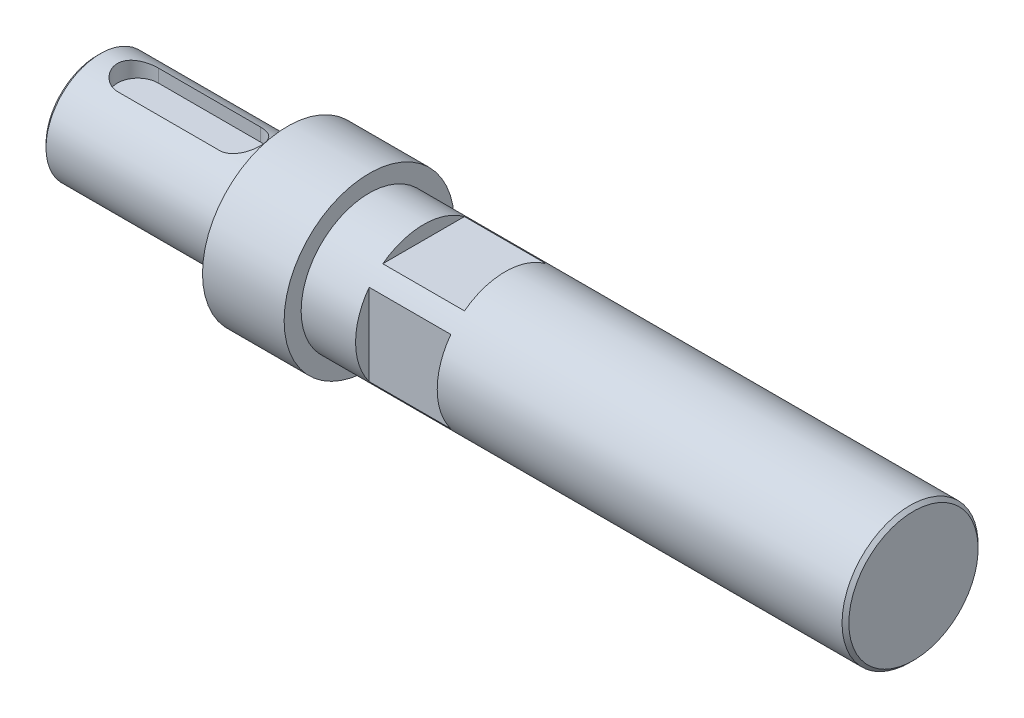
SolidWorks part; units mm, degrees
material "Простая углеродистая сталь"
ref_plane "Спереди" through (0, 0, 0) normal (0, 0, 1) x (1, 0, 0)
ref_plane "Сверху" through (0, 0, 0) normal (0, 1, 0) x (1, 0, 0)
ref_plane "Справа" through (0, 0, 0) normal (1, 0, 0) x (0, 0, -1)
sketch "Эскиз1" plane through (0, 0, 0) normal (0, 0, 1) x (1, 0, 0)
  line L0 (-178.3226, 0) -> (65.8065, 0) construction
  line L1 (0, 0) -> (0, 19)
  line L2 (-1, 20) -> (-160, 20)
  line L3 (-160, 20) -> (-160, 25)
  line L4 (-160, 25) -> (-184, 25)
  line L5 (-184, 25) -> (-184, 16)
  line L6 (-184, 16) -> (-239, 16)
  line L7 (-240, 15) -> (-240, 0)
  line L8 (-240, 0) -> (0, 0)
  line L9 (0, 19) -> (-1, 20)
  line L10 (-239, 16) -> (-240, 15)
  point P4 (0, 20)
  point P10 (-240, 16)
  dimension "D1" = 40
  dimension "D2" = 32
  dimension "D3" = 50
  dimension "D4" = 240
  dimension "D5" = 160
  dimension "D6" = 24
  dimension "D7" = 1
  dimension "D8" = 45
  dimension "D9" = 1
  dimension "D10" = 45
revolve "Повернуть1" add sketch "Эскиз1" angle 360 about L0
ref_plane "Плоскость1" through (-144, 0, 0) normal (1, 0, 0) x (0, 0, -1)
sketch "Эскиз2" plane through (-144, 0, 0) normal (1, 0, 0) x (0, 0, -1)
  line L1 (-16, -16) -> (16, -16)
  line L2 (-16, -16) -> (-16, 16)
  line L3 (-16, 16) -> (16, 16)
  line L4 (16, -16) -> (16, 16)
  line L5 (-16, -16) -> (16, 16) construction
  line L6 (-16, 16) -> (16, -16) construction
  point P0 (0, 0)
  dimension "D1" = 32
extrude "Вырез-Вытянуть1" cut sketch "Эскиз2" along normal blind 24 flip side to cut
ref_plane "Плоскость2" through (0, 16, 0) normal (0, 1, 0) x (1, 0, 0)
sketch "Эскиз3" plane through (0, 16, 0) normal (0, 1, 0) x (1, 0, 0)
  line L0 (-228, 0) -> (-198, 0) construction
  line L1 (-228, 6) -> (-198, 6)
  line L2 (-228, -6) -> (-198, -6)
  line L3 (-240, 15) -> (-240, -15) construction
  arc A0 (-228, 6) -> (-228, -6) centre (-228, 0) ccw
  arc A1 (-198, -6) -> (-198, 6) centre (-198, 0) ccw
  point P3 (-213, 0)
  dimension "D1" = 12
  dimension "D2" = 30
  dimension "D3" = 12
extrude "Вырез-Вытянуть2" cut sketch "Эскиз3" against normal blind 5
